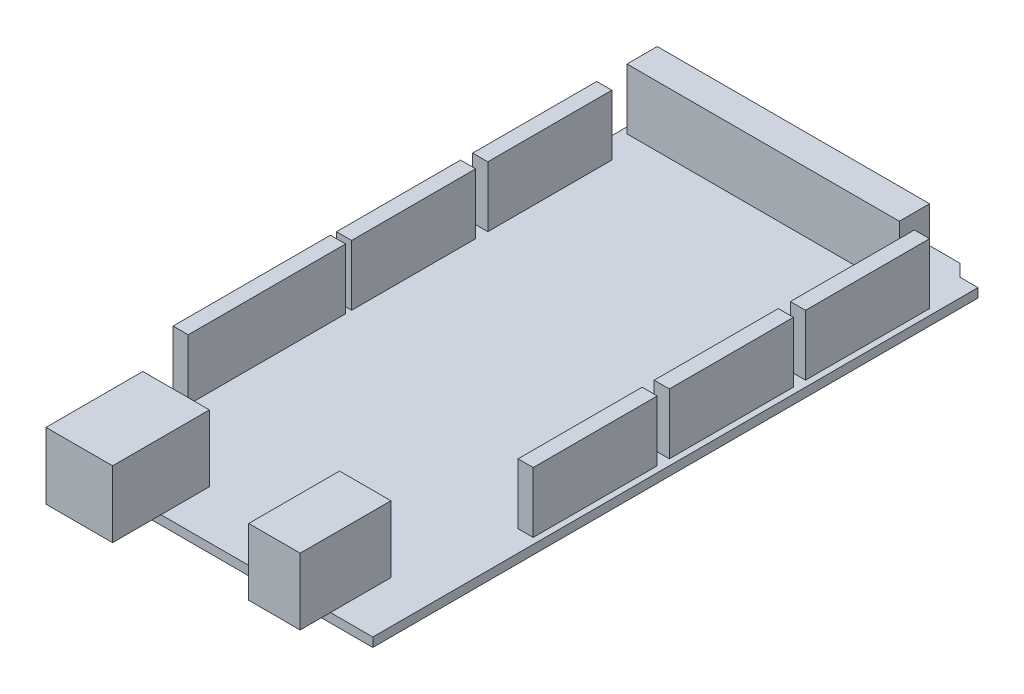
SolidWorks part; units mm, degrees
ref_plane "Front Plane" through (0, 0, 0) normal (0, 0, 1) x (1, 0, 0)
ref_plane "Top Plane" through (0, 0, 0) normal (0, 1, 0) x (1, 0, 0)
ref_plane "Right Plane" through (0, 0, 0) normal (1, 0, 0) x (0, 0, -1)
sketch "Sketch1" plane through (0, 0, 0) normal (0, 1, 0) x (1, 0, 0)
  line L0 (-26, 48.5) -> (-14, 48.5)
  line L1 (-11, 52) -> (21, 52)
  line L2 (-26, 48.5) -> (-26, -50)
  line L3 (-26, -50) -> (26, -50)
  line L4 (26, 50) -> (26, -50)
  line L5 (26, 50) -> (23, 50)
  line L6 (23, 50) -> (21, 52)
  line L7 (-14, 48.5) -> (-11, 52)
  point P0 (0, 0)
  point P2 (26, 0)
  point P12 (0, -50)
  dimension "D1" = 102
  dimension "D2" = 52
  dimension "D3" = 3.5
  dimension "D4" = 12
  dimension "D5" = 15
  dimension "D6" = 2
  dimension "D7" = 3
  dimension "D8" = 5
extrude "Boss-Extrude1" add sketch "Sketch1" along normal blind 1.5
sketch "Sketch2" plane through (0, 1.5, 0) normal (0, 1, 0) x (1, 0, 0)
  line L0 (-25, 48) -> (20, 48)
  line L1 (20, 48) -> (20, 43)
  line L2 (20, 43) -> (-25, 43)
  line L3 (-25, 43) -> (-25, 48)
  line L4 (-26, 48.5) -> (-26, -50) construction
  line L5 (26, -50) -> (26, 50) construction
  line L6 (21, 52) -> (-11, 52) construction
  line L7 (-25, 38) -> (-25, 17.5)
  line L8 (-25, 17.5) -> (-22.5, 17.5)
  line L9 (-22.5, 17.5) -> (-22.5, 38)
  line L10 (-22.5, 38) -> (-25, 38)
  line L11 (-25, 15.5) -> (-25, -5)
  line L12 (-25, -5) -> (-22.5, -5)
  line L13 (-22.5, -5) -> (-22.5, 15.5)
  line L14 (-22.5, 15.5) -> (-25, 15.5)
  line L15 (-25, -6) -> (-25, -32)
  line L16 (-25, -32) -> (-22.5, -32)
  line L17 (-22.5, -32) -> (-22.5, -6)
  line L18 (-22.5, -6) -> (-25, -6)
  line L19 (22.5, 20.5) -> (22.5, 0)
  line L20 (22.5, 0) -> (25, 0)
  line L21 (22.5, 43) -> (25, 43)
  line L22 (25, 43) -> (25, 22.5)
  line L23 (25, 22.5) -> (22.5, 22.5)
  line L24 (22.5, 22.5) -> (22.5, 43)
  line L25 (25, 0) -> (25, 20.5)
  line L26 (25, 20.5) -> (22.5, 20.5)
  line L27 (22.5, -2) -> (22.5, -22.5)
  line L28 (22.5, -22.5) -> (25, -22.5)
  line L29 (25, -22.5) -> (25, -2)
  line L30 (25, -2) -> (22.5, -2)
  dimension "D1" = 5
  dimension "D2" = 1
  dimension "D3" = 6
  dimension "D4" = 4
  dimension "D5" = 5
  dimension "D6" = 20.5
  dimension "D7" = 2.5
  dimension "D8" = 20.5
  dimension "D9" = 2
  dimension "D10" = 26
  dimension "D11" = 1
  dimension "D12" = 20.5
  dimension "D13" = 2.5
  dimension "D14" = 1
  dimension "D15" = 2
  dimension "D16" = 20.5
  dimension "D17" = 2
  dimension "D18" = 20.5
extrude "Boss-Extrude2" add sketch "Sketch2" along normal blind 10
sketch "Sketch3" plane through (0, 1.5, 0) normal (0, 1, 0) x (1, 0, 0)
  line L0 (19, -40) -> (10.5, -40)
  line L1 (10.5, -40) -> (10.5, -55)
  line L2 (10.5, -55) -> (19, -55)
  line L3 (19, -55) -> (19, -40)
  line L4 (26, -50) -> (26, 50) construction
  line L5 (-26, -50) -> (26, -50) construction
  dimension "D1" = 7
  dimension "D2" = 8.5
  dimension "D3" = 15
  dimension "D4" = 10
extrude "Boss-Extrude3" add sketch "Sketch3" along normal blind 11
sketch "Sketch4" plane through (0, 1.5, 0) normal (0, 1, 0) x (1, 0, 0)
  line L0 (-26, 48.5) -> (-26, -50) construction
  line L1 (-20, -42) -> (-9, -42)
  line L2 (-20, -42) -> (-20, -58)
  line L3 (-20, -58) -> (-9, -58)
  line L4 (-9, -42) -> (-9, -58)
  line L5 (-26, -50) -> (10.5, -50) construction
  dimension "D1" = 6
  dimension "D2" = 11
  dimension "D3" = 16
  dimension "D4" = 8
extrude "Boss-Extrude4" add sketch "Sketch4" along normal blind 11
